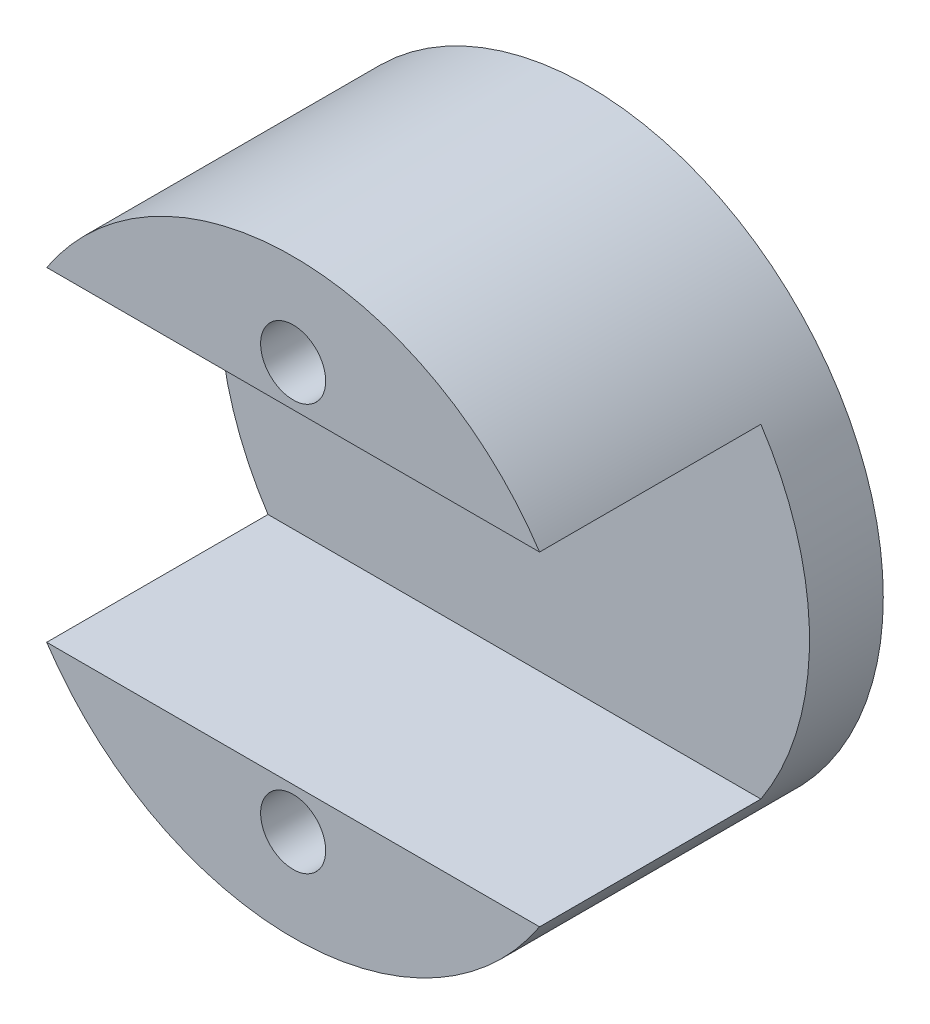
SolidWorks part; units mm, degrees
ref_plane "Front Plane" through (0, 0, 0) normal (0, 0, 1) x (1, 0, 0)
ref_plane "Top Plane" through (0, 0, 0) normal (0, 1, 0) x (1, 0, 0)
ref_plane "Right Plane" through (0, 0, 0) normal (1, 0, 0) x (0, 0, -1)
sketch "Sketch1" plane through (0, 0, 0) normal (0, 0, 1) x (1, 0, 0)
  circle A0 centre (0, 0) radius 25.4
  dimension "D1" = 50.8
extrude "Boss-Extrude1" add sketch "Sketch1" along normal blind 25.4
sketch "Sketch2" plane through (0, 0, 25.4) normal (0, 0, 1) x (1, 0, 0)
  line L0 (-21.9458, 13.97) -> (21.9458, 13.97)
  line L1 (-21.9458, -13.97) -> (21.9458, -13.97)
  line L2 (0, 13.97) -> (0, -13.97) construction
  arc A0 (-21.9458, 13.97) -> (-21.9458, -13.97) centre (0, 0) ccw
  arc A1 (21.9458, -13.97) -> (21.9458, 13.97) centre (0, 0) ccw
  point P9 (0, 0)
  dimension "D1" = 27.94
extrude "Cut-Extrude1" cut sketch "Sketch2" against normal blind 19.05
sketch "Sketch3" plane through (0, 0, 25.4) normal (0, 0, 1) x (1, 0, 0)
  line L0 (0, 25.4) -> (0, -25.4) construction
  line L2 (-2.8, 17.5) -> (-2.8, -17.5) construction
  arc A0 (21.2132, 13.97) -> (-21.2132, 13.97) centre (0, 0) ccw construction
  arc A1 (-21.2132, -13.97) -> (21.2132, -13.97) centre (0, 0) ccw construction
  circle A2 centre (0, 17.5) radius 2.8
  circle A3 centre (0, -17.5) radius 2.8
  point P12 (-2.8, 0)
  dimension "D1" = 5.6
  dimension "D2" = 35
extrude "Cut-Extrude2" cut sketch "Sketch3" against normal through all
